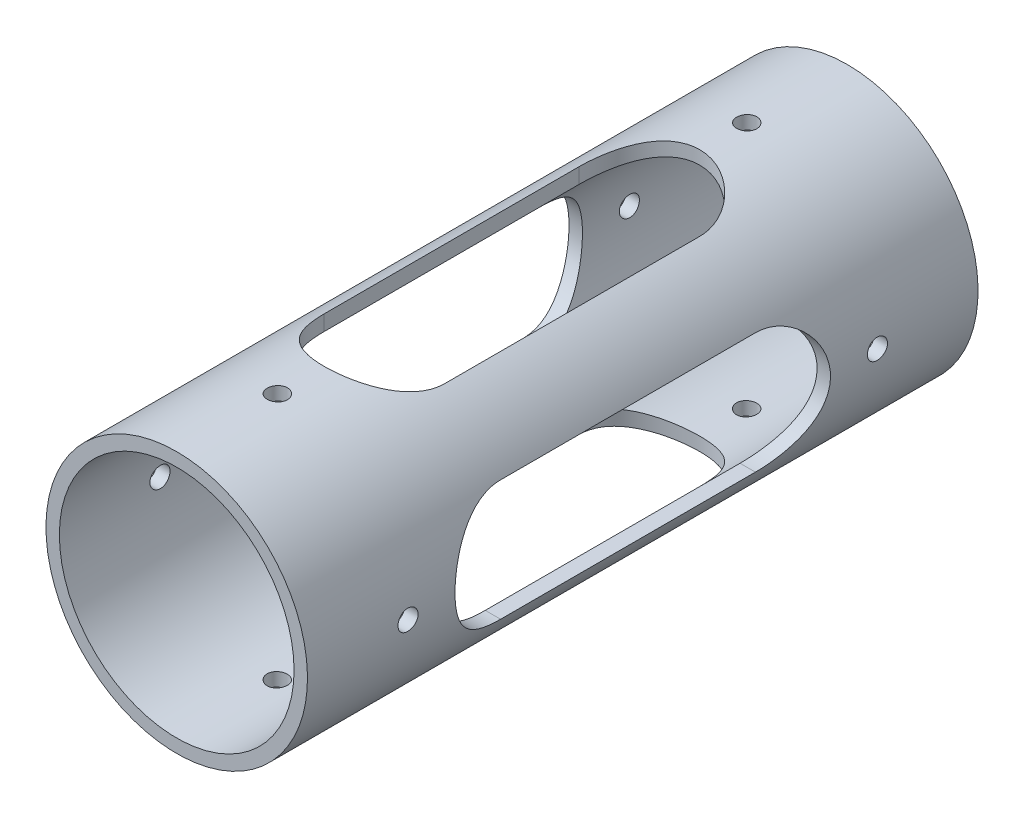
SolidWorks part; units mm, degrees
ref_plane "Front Plane" through (0, 0, 0) normal (1, 0, 0) x (0, 1, 0)
ref_plane "Top Plane" through (0, 0, 0) normal (0, 0, 1) x (0, 1, 0)
ref_plane "Right Plane" through (0, 0, 0) normal (0, 1, 0) x (-1, 0, 0)
sketch "Sketch1" plane through (0, 0, 0) normal (0, 0, 1) x (0, 1, 0)
  circle A0 centre (0, 0) radius 17.5
  dimension "D1" = 35
extrude "Extrude-Thin1" add sketch "Sketch1" along normal blind 100 thin
sketch "Sketch2" plane through (0, 0, 0) normal (0, 1, 0) x (-1, 0, 0)
  line L0 (17.5, 100) -> (-17.5, 100) construction
  circle A0 centre (0, 85) radius 1.5
  circle A1 centre (0, 15) radius 1.5
  dimension "D1" = 3
  dimension "D2" = 3
  dimension "D3" = 15
  dimension "D4" = 15
extrude "Cut-Extrude1" cut sketch "Sketch2" against normal through all both and the other way through all
sketch "Sketch3" plane through (0, 0, 0) normal (0, 1, 0) x (-1, 0, 0)
  line L0 (0, 69) -> (0, 31) construction
  line L1 (9, 69) -> (9, 31)
  line L2 (-9, 69) -> (-9, 31)
  arc A0 (9, 69) -> (-9, 69) centre (0, 69) ccw
  arc A1 (-9, 31) -> (9, 31) centre (0, 31) ccw
  circle A2 centre (0, 85) radius 1.5 construction
  circle A3 centre (0, 15) radius 1.5 construction
  point P3 (0, 50)
  dimension "D1" = 9
  dimension "D2" = 16
  dimension "D3" = 16
extrude "Cut-Extrude2" cut sketch "Sketch3" against normal through all both and the other way through all
pattern_circular "CirPattern1" count 2 every 90 about axis through (0, 0, 100) along (0, 0, -1) of "Cut-Extrude1", "Cut-Extrude2"
